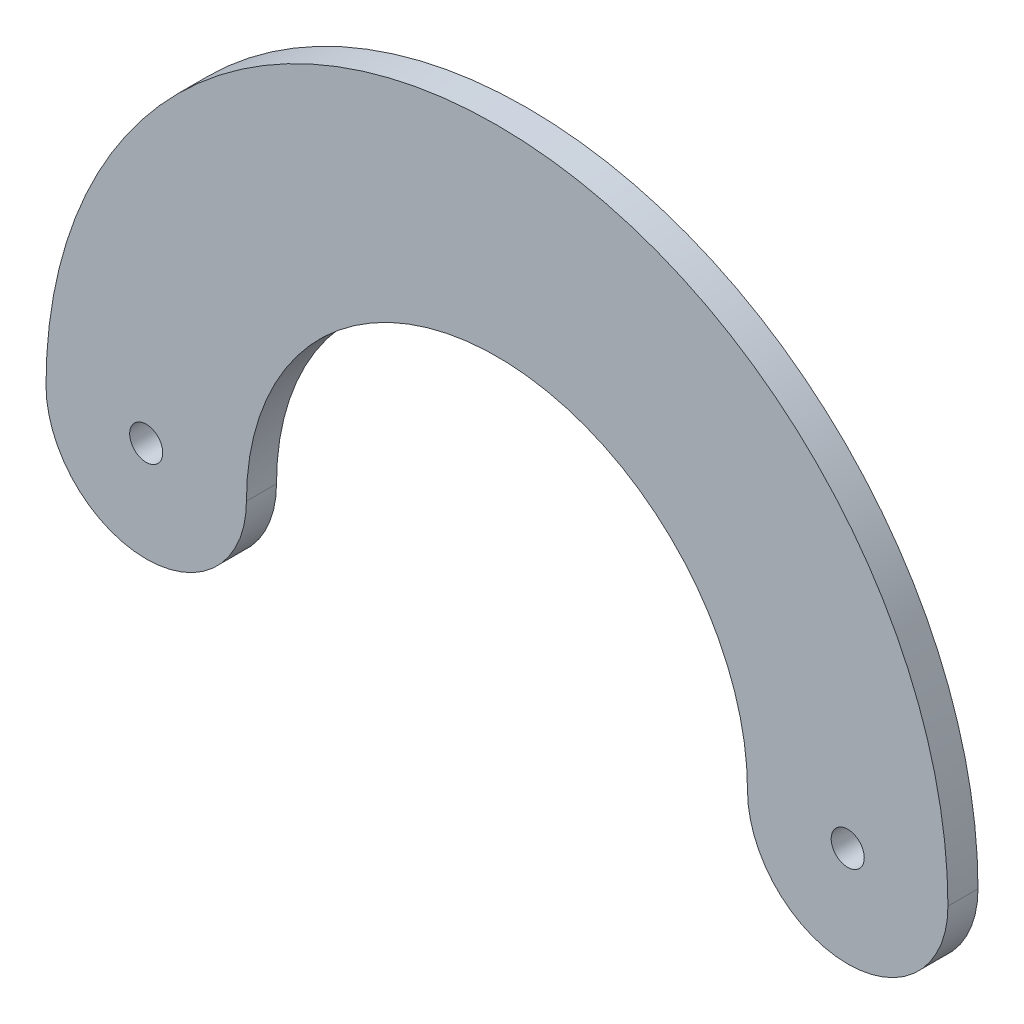
SolidWorks part; units mm, degrees
material "Thornel Mat VMA"
ref_plane "前视基准面" through (0, 0, 0) normal (0, 0, 1) x (1, 0, 0)
ref_plane "上视基准面" through (0, 0, 0) normal (0, 1, 0) x (1, 0, 0)
ref_plane "右视基准面" through (0, 0, 0) normal (1, 0, 0) x (0, 0, -1)
sketch "草图1" plane through (0, 0, 0) normal (0, 0, 1) x (1, 0, 0)
  arc A0 (-35, 0) -> (35, 0) centre (0, 0) cw
  arc A1 (-25, 0) -> (25, 0) centre (0, 0) cw
  arc A2 (-45, 0) -> (45, 0) centre (0, 0) cw
  arc A3 (-25, 0) -> (-45, 0) centre (-35, 0) cw
  arc A4 (25, 0) -> (45, 0) centre (35, 0) ccw
  circle A5 centre (-35, 0) radius 1.65
  circle A6 centre (35, 0) radius 1.65
  dimension "D1" = 35
  dimension "D4" = 3.3
  dimension "D5" = 3.3
  dimension "D2" = 10
  dimension "D3" = 10
extrude "凸台-拉伸1" add sketch "草图1" along normal blind 3
